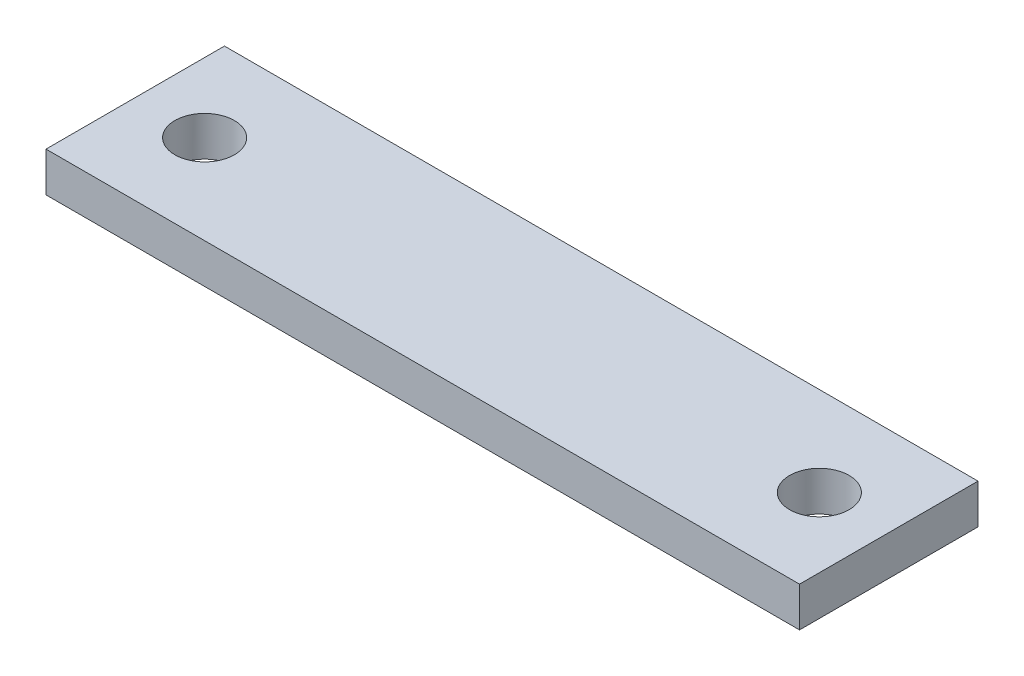
SolidWorks part; units mm, degrees
material "PET"
ref_plane "Alzado" through (0, 0, 0) normal (0, 0, 1) x (1, 0, 0)
ref_plane "Planta" through (0, 0, 0) normal (0, 1, 0) x (1, 0, 0)
ref_plane "Vista lateral" through (0, 0, 0) normal (1, 0, 0) x (0, 0, -1)
sketch "Croquis1" plane through (0, 0, 0) normal (0, 1, 0) x (1, 0, 0)
  line L1 (-19, -4.5) -> (19, -4.5)
  line L2 (-19, -4.5) -> (-19, 4.5)
  line L3 (-19, 4.5) -> (19, 4.5)
  line L4 (19, -4.5) -> (19, 4.5)
  line L5 (-19, -4.5) -> (19, 4.5) construction
  line L6 (-19, 4.5) -> (19, -4.5) construction
  point P0 (0, 0)
  dimension "D1" = 38
  dimension "D2" = 9
extrude "Saliente-Extruir1" add sketch "Croquis1" along normal blind 2
sketch "Croquis2" plane through (0, 2, 0) normal (0, 1, 0) x (1, 0, 0)
  line L0 (-19, -4.5) -> (-12, -4.5) construction
  line L1 (-19, -4.5) -> (19, -4.5) construction
  line L2 (-12, -4.5) -> (-19, 4.5) construction
  line L4 (0, -1.1) -> (0, 1.1) construction
  circle A0 centre (-15.5, 0) radius 1.5
  circle A1 centre (15.5, 0) radius 1.5
  dimension "D2" = 3
  dimension "D1" = 7
extrude "Cortar-Extruir1" cut sketch "Croquis2" against normal up to next
